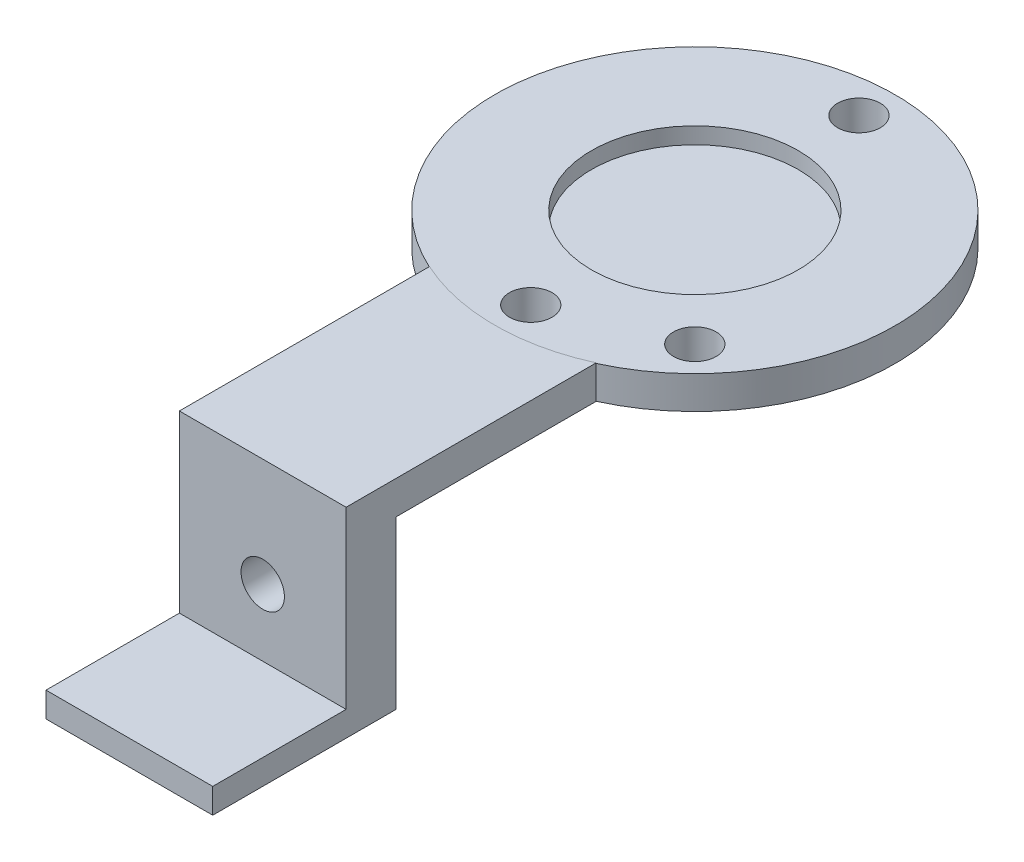
SolidWorks part; units mm, degrees
ref_plane "Front Plane" through (0, 0, 0) normal (0, 0, 1) x (1, 0, 0)
ref_plane "Top Plane" through (0, 0, 0) normal (0, 1, 0) x (1, 0, 0)
ref_plane "Right Plane" through (0, 0, 0) normal (1, 0, 0) x (0, 0, -1)
sketch "Sketch1" plane through (0, 0, 0) normal (0, 1, 0) x (1, 0, 0)
  circle A0 centre (0, 0) radius 30.5
extrude "Boss-Extrude1" add sketch "Sketch1" along normal blind 5
sketch "Sketch2" plane through (0, 5, 0) normal (0, 1, 0) x (1, 0, 0)
  circle A0 centre (0, 0) radius 15.75
extrude "Cut-Extrude1" cut sketch "Sketch2" against normal blind 2.5
sketch "Sketch3" plane through (0, 0, 0) normal (0, -1, 0) x (1, 0, 0)
  circle A0 centre (0, 0) radius 15.75
extrude "Boss-Extrude2" add sketch "Sketch3" along normal blind 2.5
sketch "Sketch4" plane through (0, 0, 0) normal (0, -1, 0) x (-1, 0, 0)
  circle A0 centre (0, 25) radius 3.25
  point P0 (0, 25)
  dimension "D1" = 25
extrude "Cut-Extrude2" cut sketch "Sketch4" against normal blind 5.08
sketch "Sketch5" plane through (0, 0, 0) normal (0, -1, 0) x (1, 0, 0)
  circle A0 centre (0, 25) radius 3.25
  point P0 (0, 25)
  dimension "D1" = 25
extrude "Cut-Extrude3" cut sketch "Sketch5" against normal blind 5.08
sketch "Sketch6" plane through (0, 0, 0) normal (0, -1, 0) x (1, 0, 0)
  circle A0 centre (0, 25) radius 3.25 construction
  circle A1 centre (17.6745, 17.6809) radius 3.25
  point P0 (17.6745, 17.6809)
  dimension "D1" = 25
  dimension "D2" = 19.13
extrude "Cut-Extrude4" cut sketch "Sketch6" against normal blind 5.08
sketch "Sketch7" plane through (0, 0, 0) normal (0, -1, 0) x (-1, 0, 0)
  line L0 (0, 0) -> (0, -30.5)
  line L1 (-12.7, -27.7301) -> (12.7, -27.7301)
  line L2 (-12.7, -27.7301) -> (-12.7, -65.8301)
  line L3 (-12.7, -65.8301) -> (12.7, -65.8301)
  line L4 (12.7, -27.7301) -> (12.7, -65.8301)
  circle A0 centre (0, 0) radius 30.5 construction
  circle M10 centre (0, 0) radius 30.5
  dimension "D1" = 25.4
  dimension "D2" = 12.7
  dimension "D3" = 38.1
extrude "Boss-Extrude3" add sketch "Sketch7" against normal blind 5.08 contours L4 L2 L3 M10
sketch "Sketch8" plane through (0, 0, 0) normal (0, -1, 0) x (1, 0, 0)
  line L0 (12.7, 27.7301) -> (12.7, 65.8301) construction
  line L1 (12.7, 58.2101) -> (-12.7, 58.2101)
  line L2 (12.7, 58.2101) -> (12.7, 65.8301)
  line L3 (12.7, 65.8301) -> (-12.7, 65.8301)
  line L4 (-12.7, 58.2101) -> (-12.7, 65.8301)
  dimension "D1" = 7.62
extrude "Boss-Extrude4" add sketch "Sketch8" along normal blind 25.4
sketch "Sketch9" plane through (0, 0, 65.8301) normal (0, 0, 1) x (1, 0, 0)
  line L0 (-12.7, 5.08) -> (-12.7, -25.4) construction
  line L1 (12.7, -25.4) -> (-12.7, -25.4)
  line L2 (12.7, -25.4) -> (12.7, -21.59)
  line L3 (12.7, -21.59) -> (-12.7, -21.59)
  line L4 (-12.7, -25.4) -> (-12.7, -21.59)
  dimension "D1" = 3.81
extrude "Boss-Extrude5" add sketch "Sketch9" along normal blind 20.32
sketch "Sketch10" plane through (0, 0, 58.2101) normal (0, 0, -1) x (-1, 0, 0)
  line L0 (0, -25.4) -> (0, 0)
  line L1 (12.7, -25.4) -> (-12.7, -25.4) construction
  line L2 (12.7, 0) -> (-12.7, 0) construction
  circle A0 centre (0, -11.43) radius 3.302
  dimension "D1" = 13.97
extrude "Cut-Extrude5" cut sketch "Sketch10" against normal blind 7.62 contours L0 A0 | L0 A0
sketch "Sketch11" plane through (0, 0, 58.2101) normal (0, 0, -1) x (-1, 0, 0)
  circle A0 centre (0, -11.43) radius 4.826
extrude "Cut-Extrude6" cut sketch "Sketch11" against normal blind 2.54
